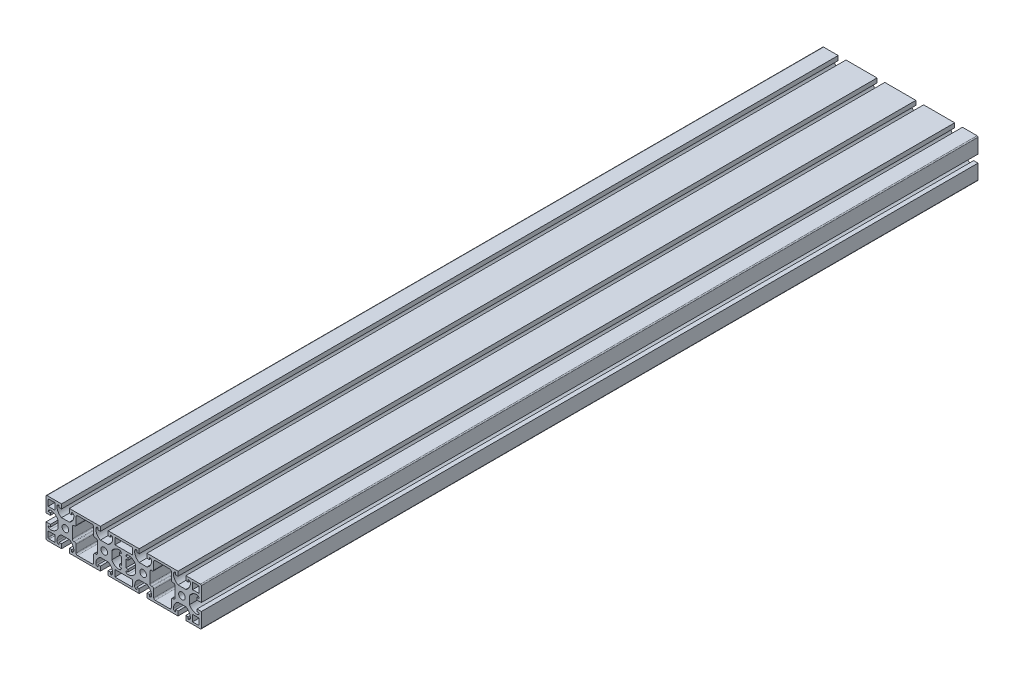
SolidWorks part; units mm, degrees
material "3.0255 (EN-AW 1350A)"
ref_plane "Płaszczyzna przednia" through (0, 0, 0) normal (0, 0, 1) x (1, 0, 0)
ref_plane "Płaszczyzna górna" through (0, 0, 0) normal (0, 1, 0) x (1, 0, 0)
ref_plane "Płaszczyzna prawa" through (0, 0, 0) normal (1, 0, 0) x (0, 0, -1)
sketch "Szkic1" plane through (0, 0, 0) normal (0, 0, 1) x (1, 0, 0)
  line L0 (0, 20) -> (0, -20) construction
  line L1 (-51.8865, 0) -> (40, 0) construction
  line L4 (-40, -20) -> (-40, 20)
  line L7 (-40, -20) -> (0, 0) construction
  line L8 (-40, 20) -> (40, -20) construction
  line L13 (20, 20) -> (20, 0) construction
  line L15 (24, 20) -> (24, 15.5)
  line L16 (24, 15.5) -> (26.4714, 15.5)
  line L21 (16, 15.5) -> (13.5286, 15.5)
  line L23 (16, 20) -> (13.5286, 20)
  line L24 (16, 20) -> (16, 15.5)
  line L25 (16, 7.75) -> (24, 7.75)
  line L26 (13.5286, 15.5) -> (13.5286, 17.75)
  line L27 (26.4714, 15.5) -> (26.4714, 17.75)
  line L28 (-24, 20) -> (-24, 15.5)
  line L29 (-26.4714, 15.5) -> (-26.4714, 17.75)
  line L30 (-24, 15.5) -> (-26.4714, 15.5)
  line L31 (-13.5286, 15.5) -> (-13.5286, 17.75)
  line L32 (-16, 15.5) -> (-13.5286, 15.5)
  line L33 (-16, 20) -> (-16, 15.5)
  line L34 (-16, 7.75) -> (-24, 7.75)
  line L35 (20, -20) -> (20, 0) construction
  line L36 (-40, -20) -> (0, 0) construction
  line L37 (-40, 20) -> (40, -20) construction
  line L38 (30.9714, -17.75) -> (36.75, -17.75)
  line L39 (-16, -7.75) -> (-24, -7.75)
  line L40 (-16, -20) -> (-16, -15.5)
  line L41 (-16, -15.5) -> (-13.5286, -15.5)
  line L42 (-13.5286, -15.5) -> (-13.5286, -17.75)
  line L43 (-24, -15.5) -> (-26.4714, -15.5)
  line L44 (-26.4714, -15.5) -> (-26.4714, -17.75)
  line L45 (-24, -20) -> (-24, -15.5)
  line L46 (26.4714, -15.5) -> (26.4714, -17.75)
  line L47 (13.5286, -15.5) -> (13.5286, -17.75)
  line L48 (16, -7.75) -> (24, -7.75)
  line L49 (16, -20) -> (16, -15.5)
  line L50 (16, -15.5) -> (13.5286, -15.5)
  line L51 (24, -15.5) -> (26.4714, -15.5)
  line L52 (24, -20) -> (24, -15.5)
  line L53 (40, -20) -> (0, 20) construction
  line L54 (35.5, 6.4714) -> (37.75, 6.4714)
  line L55 (35.5, 4) -> (35.5, 6.4714)
  line L56 (40, 4) -> (35.5, 4)
  line L57 (40, -4) -> (35.5, -4)
  line L58 (35.5, -4) -> (35.5, -6.4714)
  line L59 (35.5, -6.4714) -> (37.75, -6.4714)
  line L60 (27.75, 4) -> (27.75, -4)
  line L61 (-35.5, -6.4714) -> (-37.75, -6.4714)
  line L62 (-37.75, -4) -> (-35.5, -4)
  line L63 (-35.5, -4) -> (-35.5, -6.4714)
  line L64 (-35.5, 4) -> (-35.5, 6.4714)
  line L65 (-35.5, 6.4714) -> (-37.75, 6.4714)
  line L66 (-37.75, 4) -> (-35.5, 4)
  line L67 (-27.75, 4) -> (-27.75, -4)
  line L68 (-37.75, 4) -> (-37.75, -4)
  line L69 (40, -4) -> (40, -19)
  line L70 (40, 19) -> (40, 4)
  line L71 (-40, -20) -> (-24, -20)
  line L72 (-16, -20) -> (16, -20)
  line L73 (24, -20) -> (39, -20)
  line L74 (13.5286, 20) -> (-16, 20)
  line L75 (-24, 20) -> (-40, 20)
  line L76 (24, 20) -> (39, 20)
  line L77 (10.5286, 7.0902) -> (11.4095, 7.0902)
  line L78 (-7.5286, -17.75) -> (7.5286, -17.75)
  line L79 (-9.0286, -16.25) -> (-9.0286, -8.5902)
  line L80 (-7.5286, 17.75) -> (7.5286, 17.75)
  line L81 (9.0286, -16.25) -> (9.0286, -8.5902)
  line L82 (-9.0286, -17.75) -> (9.0286, 17.75) construction
  line L83 (-9.0286, 17.75) -> (9.0286, -17.75) construction
  line L84 (-11.4095, -7.0902) -> (-10.5286, -7.0902)
  line L85 (-12.9095, -5.5902) -> (-12.9095, 5.5902)
  line L86 (-11.4095, 7.0902) -> (-10.5286, 7.0902)
  line L87 (12.9095, -5.5902) -> (12.9095, 5.5902)
  line L88 (-12.9095, -7.0902) -> (0, 0) construction
  line L89 (-12.9095, 7.0902) -> (12.9095, -7.0902) construction
  line L90 (-9.0286, 8.5902) -> (-9.0286, 16.25)
  line L91 (-9.0286, 4.5143) -> (-9.0286, 4.9587)
  line L92 (-9.0286, -4.9587) -> (-9.0286, -4.5143)
  line L93 (9.0286, 8.5902) -> (9.0286, 16.25)
  line L94 (10.5286, -7.0902) -> (11.4095, -7.0902)
  line L96 (0, 0) -> (12.9095, 7.0902) construction
  line L98 (37.75, -10.9714) -> (37.75, -16.75)
  line L99 (30.9714, 10.9714) -> (37.75, 10.9714)
  line L100 (30.9714, 10.9714) -> (30.9714, 17.75)
  line L101 (30.9714, 17.75) -> (36.75, 17.75)
  line L102 (37.75, 10.9714) -> (37.75, 16.75)
  line L103 (30.9714, 10.9714) -> (37.75, 17.75) construction
  line L104 (30.9714, 17.75) -> (37.75, 10.9714) construction
  line L105 (30.9714, -10.9714) -> (37.75, -10.9714)
  line L106 (30.9714, -10.9714) -> (30.9714, -17.75)
  line L107 (-30.9714, -10.9714) -> (-30.9714, -17.75)
  line L108 (-30.9714, -10.9714) -> (-37.75, -10.9714)
  line L109 (-37.75, -10.9714) -> (-37.75, -16.75)
  line L110 (-30.9714, -17.75) -> (-36.75, -17.75)
  line L111 (-30.9714, 17.75) -> (-36.75, 17.75)
  line L112 (-37.75, 10.9714) -> (-37.75, 16.75)
  line L113 (-30.9714, 10.9714) -> (-37.75, 10.9714)
  line L114 (-30.9714, 10.9714) -> (-30.9714, 17.75)
  line L115 (-40, 52.1634) -> (-40, -64.8993) construction
  line L116 (-110.9714, 17.75) -> (-117.75, 10.9714) construction
  line L117 (-110.9714, 10.9714) -> (-117.75, 17.75) construction
  line L118 (-80, 0) -> (-92.9095, 7.0902) construction
  line L119 (-67.0905, 7.0902) -> (-92.9095, -7.0902) construction
  line L120 (-67.0905, -7.0902) -> (-80, 0) construction
  line L121 (-70.9714, 17.75) -> (-89.0286, -17.75) construction
  line L122 (-70.9714, -17.75) -> (-89.0286, 17.75) construction
  line L123 (-120, -20) -> (-80, 20) construction
  line L124 (-40, 20) -> (-120, -20) construction
  line L125 (-40, -20) -> (-80, 0) construction
  line L126 (-100, -20) -> (-100, 0) construction
  line L127 (-100, 20) -> (-100, 0) construction
  line L128 (-40, 20) -> (-120, -20) construction
  line L129 (-40, -20) -> (-80, 0) construction
  line L130 (-28.1135, 0) -> (-120, 0) construction
  line L131 (-80, 20) -> (-80, -20) construction
  line L132 (-49.0286, 10.9714) -> (-49.0286, 17.75)
  line L133 (-49.0286, 10.9714) -> (-42.25, 10.9714)
  line L134 (-42.25, 10.9714) -> (-42.25, 16.75)
  line L135 (-49.0286, 17.75) -> (-43.25, 17.75)
  line L136 (-49.0286, -17.75) -> (-43.25, -17.75)
  line L137 (-42.25, -10.9714) -> (-42.25, -16.75)
  line L138 (-49.0286, -10.9714) -> (-42.25, -10.9714)
  line L139 (-49.0286, -10.9714) -> (-49.0286, -17.75)
  line L140 (-110.9714, -10.9714) -> (-110.9714, -17.75)
  line L141 (-110.9714, -10.9714) -> (-117.75, -10.9714)
  line L142 (-117.75, 10.9714) -> (-117.75, 16.75)
  line L143 (-110.9714, 17.75) -> (-116.75, 17.75)
  line L144 (-110.9714, 10.9714) -> (-110.9714, 17.75)
  line L145 (-110.9714, 10.9714) -> (-117.75, 10.9714)
  line L146 (-117.75, -10.9714) -> (-117.75, -16.75)
  line L147 (-90.5286, -7.0902) -> (-91.4095, -7.0902)
  line L148 (-89.0286, 8.5902) -> (-89.0286, 16.25)
  line L149 (-70.9714, -4.9587) -> (-70.9714, -4.5143)
  line L150 (-70.9714, 4.5143) -> (-70.9714, 4.9587)
  line L151 (-70.9714, 8.5902) -> (-70.9714, 16.25)
  line L152 (-92.9095, -5.5902) -> (-92.9095, 5.5902)
  line L153 (-68.5905, 7.0902) -> (-69.4714, 7.0902)
  line L154 (-67.0905, -5.5902) -> (-67.0905, 5.5902)
  line L155 (-68.5905, -7.0902) -> (-69.4714, -7.0902)
  line L156 (-89.0286, -16.25) -> (-89.0286, -8.5902)
  line L157 (-72.4714, 17.75) -> (-87.5286, 17.75)
  line L158 (-70.9714, -16.25) -> (-70.9714, -8.5902)
  line L159 (-72.4714, -17.75) -> (-87.5286, -17.75)
  line L160 (-90.5286, 7.0902) -> (-91.4095, 7.0902)
  line L161 (-104, 20) -> (-119, 20)
  line L162 (-56, 20) -> (-40, 20)
  line L163 (-93.5286, 20) -> (-64, 20)
  line L164 (-104, -20) -> (-119, -20)
  line L165 (-64, -20) -> (-96, -20)
  line L166 (-40, -20) -> (-56, -20)
  line L167 (-120, 19) -> (-120, 4)
  line L168 (-120, -4) -> (-120, -19)
  line L169 (-42.25, 4) -> (-42.25, -4)
  line L170 (-52.25, 4) -> (-52.25, -4)
  line L171 (-42.25, 4) -> (-44.5, 4)
  line L172 (-44.5, 6.4714) -> (-42.25, 6.4714)
  line L173 (-44.5, 4) -> (-44.5, 6.4714)
  line L174 (-44.5, -4) -> (-44.5, -6.4714)
  line L175 (-42.25, -4) -> (-44.5, -4)
  line L176 (-44.5, -6.4714) -> (-42.25, -6.4714)
  line L177 (-107.75, 4) -> (-107.75, -4)
  line L178 (-115.5, -6.4714) -> (-117.75, -6.4714)
  line L179 (-115.5, -4) -> (-115.5, -6.4714)
  line L180 (-120, -4) -> (-115.5, -4)
  line L181 (-120, 4) -> (-115.5, 4)
  line L182 (-115.5, 4) -> (-115.5, 6.4714)
  line L183 (-115.5, 6.4714) -> (-117.75, 6.4714)
  line L184 (-104, -20) -> (-104, -15.5)
  line L185 (-104, -15.5) -> (-106.4714, -15.5)
  line L186 (-96, -15.5) -> (-93.5286, -15.5)
  line L187 (-96, -20) -> (-96, -15.5)
  line L188 (-96, -7.75) -> (-104, -7.75)
  line L189 (-93.5286, -15.5) -> (-93.5286, -17.75)
  line L190 (-106.4714, -15.5) -> (-106.4714, -17.75)
  line L191 (-56, -20) -> (-56, -15.5)
  line L192 (-53.5286, -15.5) -> (-53.5286, -17.75)
  line L193 (-56, -15.5) -> (-53.5286, -15.5)
  line L194 (-66.4714, -15.5) -> (-66.4714, -17.75)
  line L195 (-64, -15.5) -> (-66.4714, -15.5)
  line L196 (-64, -20) -> (-64, -15.5)
  line L197 (-64, -7.75) -> (-56, -7.75)
  line L198 (-110.9714, -17.75) -> (-116.75, -17.75)
  line L199 (-64, 7.75) -> (-56, 7.75)
  line L200 (-64, 20) -> (-64, 15.5)
  line L201 (-64, 15.5) -> (-66.4714, 15.5)
  line L202 (-66.4714, 15.5) -> (-66.4714, 17.75)
  line L203 (-56, 15.5) -> (-53.5286, 15.5)
  line L204 (-53.5286, 15.5) -> (-53.5286, 17.75)
  line L205 (-56, 20) -> (-56, 15.5)
  line L206 (-106.4714, 15.5) -> (-106.4714, 17.75)
  line L207 (-93.5286, 15.5) -> (-93.5286, 17.75)
  line L208 (-96, 7.75) -> (-104, 7.75)
  line L209 (-96, 20) -> (-96, 15.5)
  line L210 (-96, 20) -> (-93.5286, 20)
  line L211 (-96, 15.5) -> (-93.5286, 15.5)
  line L212 (-104, 15.5) -> (-106.4714, 15.5)
  line L213 (-104, 20) -> (-104, 15.5)
  line L215 (-43.25, 17.75) -> (-36.75, 17.75)
  line L216 (-42.25, 10.9714) -> (-37.75, 10.9714)
  line L217 (-42.25, -10.9714) -> (-37.75, -10.9714)
  line L218 (-43.25, -17.75) -> (-36.75, -17.75)
  circle A0 centre (-20, 0) radius 3.4
  circle A1 centre (20, 0) radius 3.4
  arc A2 (26.4714, 17.75) -> (28.7214, 15.5) centre (26.4714, 15.5) cw
  arc A3 (28.7214, 15.5) -> (24, 7.75) centre (20, 15.5) cw
  arc A4 (13.5286, 17.75) -> (11.2786, 15.5) centre (13.5286, 15.5) ccw
  arc A5 (11.2786, 15.5) -> (16, 7.75) centre (20, 15.5) ccw
  arc A6 (-26.4714, 17.75) -> (-28.7214, 15.5) centre (-26.4714, 15.5) ccw
  arc A7 (-13.5286, 17.75) -> (-11.2786, 15.5) centre (-13.5286, 15.5) cw
  arc A8 (-11.2786, 15.5) -> (-16, 7.75) centre (-20, 15.5) cw
  arc A9 (-28.7214, 15.5) -> (-24, 7.75) centre (-20, 15.5) ccw
  arc A10 (-28.7214, -15.5) -> (-24, -7.75) centre (-20, -15.5) cw
  arc A11 (-11.2786, -15.5) -> (-16, -7.75) centre (-20, -15.5) ccw
  arc A12 (-13.5286, -17.75) -> (-11.2786, -15.5) centre (-13.5286, -15.5) ccw
  arc A13 (-26.4714, -17.75) -> (-28.7214, -15.5) centre (-26.4714, -15.5) cw
  arc A14 (11.2786, -15.5) -> (16, -7.75) centre (20, -15.5) cw
  arc A15 (13.5286, -17.75) -> (11.2786, -15.5) centre (13.5286, -15.5) cw
  arc A16 (28.7214, -15.5) -> (24, -7.75) centre (20, -15.5) ccw
  arc A17 (26.4714, -17.75) -> (28.7214, -15.5) centre (26.4714, -15.5) ccw
  arc A18 (35.5, 8.7214) -> (27.75, 4) centre (35.5, 0) ccw
  arc A19 (37.75, 6.4714) -> (35.5, 8.7214) centre (35.5, 6.4714) ccw
  arc A20 (37.75, -6.4714) -> (35.5, -8.7214) centre (35.5, -6.4714) cw
  arc A21 (35.5, -8.7214) -> (27.75, -4) centre (35.5, 0) cw
  arc A22 (-35.5, -8.7214) -> (-27.75, -4) centre (-35.5, 0) ccw
  arc A23 (-37.75, -6.4714) -> (-35.5, -8.7214) centre (-35.5, -6.4714) ccw
  arc A24 (-37.75, 6.4714) -> (-35.5, 8.7214) centre (-35.5, 6.4714) cw
  arc A25 (-35.5, 8.7214) -> (-27.75, 4) centre (-35.5, 0) cw
  arc A26 (-10.5286, 7.0902) -> (-9.0286, 8.5902) centre (-10.5286, 8.5902) ccw
  arc A27 (-9.0286, -8.5902) -> (-10.5286, -7.0902) centre (-10.5286, -8.5902) ccw
  arc A28 (11.4095, -7.0902) -> (12.9095, -5.5902) centre (11.4095, -5.5902) ccw
  arc A29 (9.0286, -8.5902) -> (10.5286, -7.0902) centre (10.5286, -8.5902) cw
  arc A30 (7.5286, -17.75) -> (9.0286, -16.25) centre (7.5286, -16.25) ccw
  arc A31 (-7.5286, -17.75) -> (-9.0286, -16.25) centre (-7.5286, -16.25) cw
  arc A32 (-11.4095, -7.0902) -> (-12.9095, -5.5902) centre (-11.4095, -5.5902) cw
  arc A33 (-12.9095, 5.5902) -> (-11.4095, 7.0902) centre (-11.4095, 5.5902) cw
  arc A34 (-9.0286, 16.25) -> (-7.5286, 17.75) centre (-7.5286, 16.25) cw
  arc A35 (7.5286, 17.75) -> (9.0286, 16.25) centre (7.5286, 16.25) cw
  arc A36 (11.4095, 7.0902) -> (12.9095, 5.5902) centre (11.4095, 5.5902) cw
  arc A37 (10.5286, 7.0902) -> (9.0286, 8.5902) centre (10.5286, 8.5902) cw
  arc A40 (39, -20) -> (40, -19) centre (39, -19) ccw
  arc A41 (39, 20) -> (40, 19) centre (39, 19) cw
  arc A42 (36.75, 17.75) -> (37.75, 16.75) centre (36.75, 16.75) cw
  arc A43 (36.75, -17.75) -> (37.75, -16.75) centre (36.75, -16.75) ccw
  arc A44 (-36.75, -17.75) -> (-37.75, -16.75) centre (-36.75, -16.75) cw
  arc A45 (-36.75, 17.75) -> (-37.75, 16.75) centre (-36.75, 16.75) ccw
  arc A46 (-43.25, 17.75) -> (-42.25, 16.75) centre (-43.25, 16.75) cw
  arc A47 (-43.25, -17.75) -> (-42.25, -16.75) centre (-43.25, -16.75) ccw
  arc A48 (-116.75, -17.75) -> (-117.75, -16.75) centre (-116.75, -16.75) cw
  arc A49 (-116.75, 17.75) -> (-117.75, 16.75) centre (-116.75, 16.75) ccw
  arc A50 (-119, 20) -> (-120, 19) centre (-119, 19) ccw
  arc A51 (-119, -20) -> (-120, -19) centre (-119, -19) cw
  arc A54 (-90.5286, 7.0902) -> (-89.0286, 8.5902) centre (-90.5286, 8.5902) ccw
  arc A55 (-91.4095, 7.0902) -> (-92.9095, 5.5902) centre (-91.4095, 5.5902) ccw
  arc A56 (-87.5286, 17.75) -> (-89.0286, 16.25) centre (-87.5286, 16.25) ccw
  arc A57 (-70.9714, 16.25) -> (-72.4714, 17.75) centre (-72.4714, 16.25) ccw
  arc A58 (-67.0905, 5.5902) -> (-68.5905, 7.0902) centre (-68.5905, 5.5902) ccw
  arc A59 (-68.5905, -7.0902) -> (-67.0905, -5.5902) centre (-68.5905, -5.5902) ccw
  arc A60 (-72.4714, -17.75) -> (-70.9714, -16.25) centre (-72.4714, -16.25) ccw
  arc A61 (-87.5286, -17.75) -> (-89.0286, -16.25) centre (-87.5286, -16.25) cw
  arc A62 (-89.0286, -8.5902) -> (-90.5286, -7.0902) centre (-90.5286, -8.5902) ccw
  arc A63 (-91.4095, -7.0902) -> (-92.9095, -5.5902) centre (-91.4095, -5.5902) cw
  arc A64 (-70.9714, -8.5902) -> (-69.4714, -7.0902) centre (-69.4714, -8.5902) cw
  arc A65 (-69.4714, 7.0902) -> (-70.9714, 8.5902) centre (-69.4714, 8.5902) cw
  arc A66 (-44.5, 8.7214) -> (-52.25, 4) centre (-44.5, 0) ccw
  arc A67 (-42.25, 6.4714) -> (-44.5, 8.7214) centre (-44.5, 6.4714) ccw
  arc A68 (-42.25, -6.4714) -> (-44.5, -8.7214) centre (-44.5, -6.4714) cw
  arc A69 (-44.5, -8.7214) -> (-52.25, -4) centre (-44.5, 0) cw
  arc A70 (-115.5, -8.7214) -> (-107.75, -4) centre (-115.5, 0) ccw
  arc A71 (-117.75, -6.4714) -> (-115.5, -8.7214) centre (-115.5, -6.4714) ccw
  arc A72 (-117.75, 6.4714) -> (-115.5, 8.7214) centre (-115.5, 6.4714) cw
  arc A73 (-115.5, 8.7214) -> (-107.75, 4) centre (-115.5, 0) cw
  arc A74 (-106.4714, -17.75) -> (-108.7214, -15.5) centre (-106.4714, -15.5) cw
  arc A75 (-108.7214, -15.5) -> (-104, -7.75) centre (-100, -15.5) cw
  arc A76 (-93.5286, -17.75) -> (-91.2786, -15.5) centre (-93.5286, -15.5) ccw
  arc A77 (-91.2786, -15.5) -> (-96, -7.75) centre (-100, -15.5) ccw
  arc A78 (-53.5286, -17.75) -> (-51.2786, -15.5) centre (-53.5286, -15.5) ccw
  arc A79 (-66.4714, -17.75) -> (-68.7214, -15.5) centre (-66.4714, -15.5) cw
  arc A80 (-68.7214, -15.5) -> (-64, -7.75) centre (-60, -15.5) cw
  arc A81 (-51.2786, -15.5) -> (-56, -7.75) centre (-60, -15.5) ccw
  arc A82 (-51.2786, 15.5) -> (-56, 7.75) centre (-60, 15.5) cw
  arc A83 (-68.7214, 15.5) -> (-64, 7.75) centre (-60, 15.5) ccw
  arc A84 (-66.4714, 17.75) -> (-68.7214, 15.5) centre (-66.4714, 15.5) ccw
  arc A85 (-53.5286, 17.75) -> (-51.2786, 15.5) centre (-53.5286, 15.5) cw
  arc A86 (-91.2786, 15.5) -> (-96, 7.75) centre (-100, 15.5) cw
  arc A87 (-93.5286, 17.75) -> (-91.2786, 15.5) centre (-93.5286, 15.5) cw
  arc A88 (-108.7214, 15.5) -> (-104, 7.75) centre (-100, 15.5) ccw
  arc A89 (-106.4714, 17.75) -> (-108.7214, 15.5) centre (-106.4714, 15.5) ccw
  circle A90 centre (-100, 0) radius 3.4
  circle A91 centre (-60, 0) radius 3.4
  point P0 (-40, -19.2274)
  point P5 (0, 0)
  point P16 (-40, 19.1225)
  point P17 (0, 0)
  point P30 (24, 17.75)
  point P108 (0, 0)
  point P124 (-9.0286, 7.0902)
  point P132 (9.0286, -7.0902)
  point P156 (9.0286, 7.0902)
  point P161 (40, 20)
  point P162 (34.3607, 14.3607)
  point P364 (-114.3607, 14.3607)
  point P365 (-120, 20)
  point P366 (-89.0286, 7.0902)
  point P367 (-89.0286, -7.0902)
  point P368 (-70.9714, 7.0902)
  point P369 (-80, 0)
  point P370 (-80, 0)
  point P371 (-80, 0)
  point P372 (0, 0)
  dimension "D4" = 6.8
  dimension "D5" = 12.25
  dimension "D9" = 11
  dimension "D11" = 1.5
  dimension "D16" = 1
  dimension "D1" = 80
  dimension "D2" = 40
  dimension "D3" = 40
  dimension "D6" = 2.25
  dimension "D7" = 8
  dimension "D8" = 4.5
  dimension "D10" = 14.1804
  dimension "D13" = 2.25
  dimension "D14" = 2.25
  dimension "D15" = 2.25
extrude "Dodanie-wyciągnięcie1" add sketch "Szkic1" along normal blind 800
